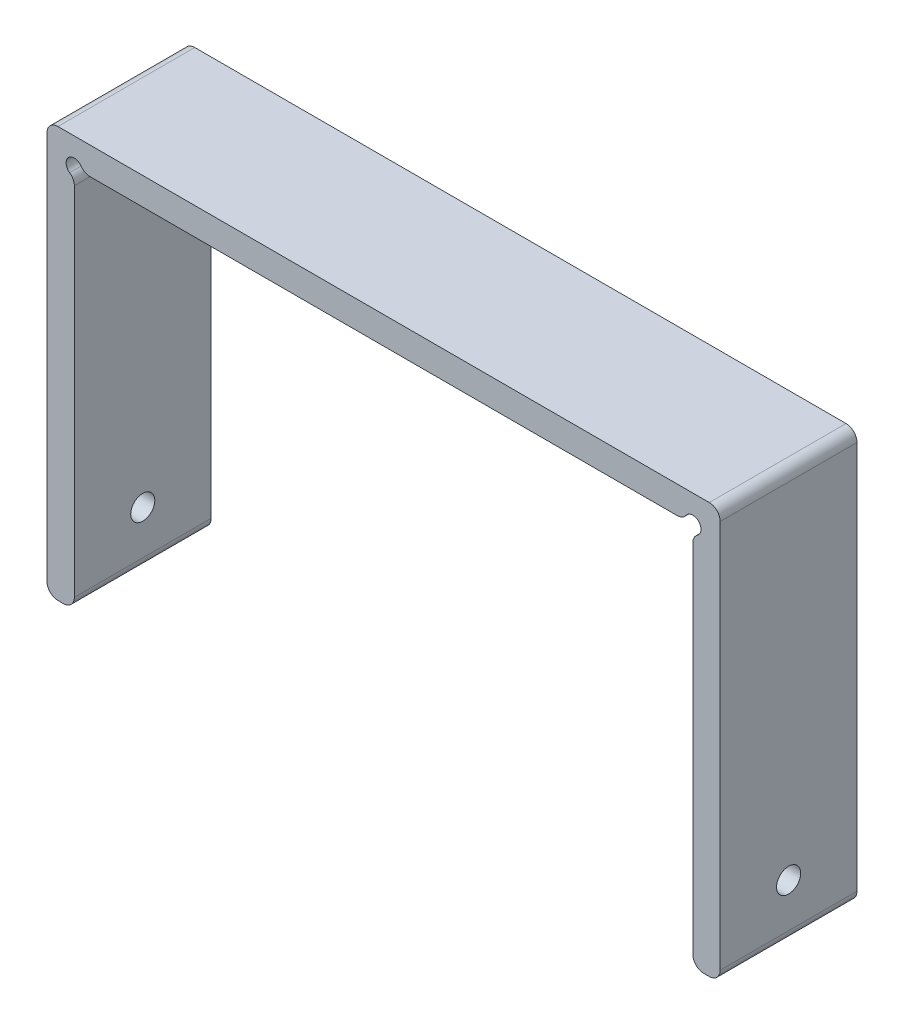
SolidWorks part; units mm, degrees
ref_plane "Front Plane" through (0, 0, 0) normal (0, 0, 1) x (1, 0, 0)
ref_plane "Top Plane" through (0, 0, 0) normal (0, 1, 0) x (1, 0, 0)
ref_plane "Right Plane" through (0, 0, 0) normal (1, 0, 0) x (0, 0, -1)
sketch "ｽｹｯﾁ1" plane through (0, 0, 0) normal (0, 0, 1) x (1, 0, 0)
  line L0 (0, 0) -> (0, 75)
  line L1 (0, 75) -> (123, 75)
  line L2 (123, 75) -> (123, 0)
  line L3 (5, 0) -> (5, 70)
  line L4 (5, 70) -> (118, 70)
  line L5 (118, 70) -> (118, 0)
  line L6 (0, 0) -> (5, 0)
  line L7 (123, 0) -> (118, 0)
  dimension "D2" = 70
  dimension "D3" = 113
  dimension "D1" = 5
extrude "ﾎﾞｽ - 押し出し1" add sketch "ｽｹｯﾁ1" along normal blind 25
sketch "ｽｹｯﾁ2" plane through (123, 0, 0) normal (1, 0, 0) x (0, 0, -1)
  line L0 (0, 0) -> (0, 75) construction
  line L1 (-25, 0) -> (0, 0) construction
  line L2 (-25, 0) -> (-25, 20) construction
  line L3 (-25, 20) -> (0, 20) construction
  line L4 (0, 0) -> (0, 20) construction
  line L5 (-12.5, 20) -> (-12.5, 0) construction
  line L6 (-25, 10) -> (0, 10) construction
  circle A0 centre (-12.5, 10) radius 2.2
  point P236 (-12.5, 10)
  dimension "D2" = 4.4
  dimension "D1" = 20
extrude "ｶｯﾄ - 押し出し2" cut sketch "ｽｹｯﾁ2" against normal through all
sketch "ｽｹｯﾁ3" plane through (0, 0, 25) normal (0, 0, 1) x (1, 0, 0)
  circle A0 centre (5, 70) radius 1.5
  circle A1 centre (118, 70) radius 1.5
  dimension "D1" = 3
extrude "ｶｯﾄ - 押し出し3" cut sketch "ｽｹｯﾁ3" against normal through all
fillet "ﾌｨﾚｯﾄ1" radius 2 10 edges at (0, 0, 12.5) (123, 75, 12.5) (123, 0, 12.5) (118, 0, 12.5) (5, 0, 12.5) (0, 75, 12.5) (5, 68.5, 12.5) (116.5, 70, 12.5) (6.5, 70, 12.5) (118, 68.5, 12.5)
